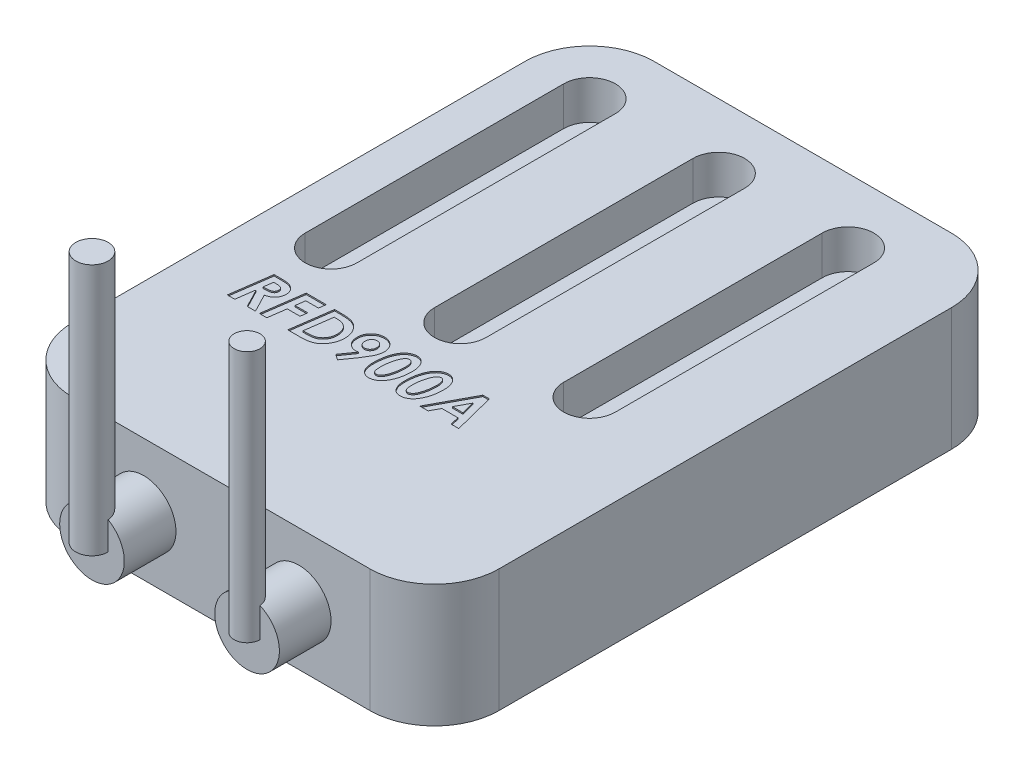
SolidWorks part; units mm, degrees
material "Alumina"
ref_plane "Front Plane" through (0, 0, 0) normal (0, 0, 1) x (1, 0, 0)
ref_plane "Top Plane" through (0, 0, 0) normal (0, 1, 0) x (1, 0, 0)
ref_plane "Right Plane" through (0, 0, 0) normal (1, 0, 0) x (0, 0, -1)
sketch "Sketch1" plane through (0, 0, 0) normal (0, 1, 0) x (1, 0, 0)
  line L1 (-16.5, -22.5) -> (16.5, -22.5)
  line L2 (-16.5, -22.5) -> (-16.5, 22.5)
  line L3 (-16.5, 22.5) -> (16.5, 22.5)
  line L4 (16.5, -22.5) -> (16.5, 22.5)
  line L5 (-16.5, -22.5) -> (16.5, 22.5) construction
  line L6 (-16.5, 22.5) -> (16.5, -22.5) construction
  point P0 (0, 0)
  dimension "D1" = 33
  dimension "D2" = 45
extrude "Boss-Extrude1" add sketch "Sketch1" along normal blind 9.5
fillet "Fillet1" radius 5 4 edges at (16.5, 4.75, -22.5) (-16.5, 4.75, -22.5) (-16.5, 4.75, 22.5) (16.5, 4.75, 22.5)
sketch "Sketch2" plane through (0, 0, 22.5) normal (0, 0, 1) x (1, 0, 0)
  line L0 (-11.5, 9.5) -> (11.5, 9.5) construction
  line L1 (0, 0) -> (0, 9.5) construction
  circle A0 centre (6, 4.5) radius 2.5
  circle A1 centre (-6, 4.5) radius 2.5
  dimension "D1" = 5
  dimension "D2" = 6
  dimension "D3" = 5
extrude "Boss-Extrude2" add sketch "Sketch2" along normal blind 4
sketch "Sketch3" plane through (0, 9.5, 0) normal (0, 1, 0) x (1, 0, 0)
  line L0 (-11.5, 17.5) -> (-11.5, -2.5) construction
  line L1 (-9.5, 17.5) -> (-9.5, -2.5)
  line L2 (-13.5, 17.5) -> (-13.5, -2.5)
  line L3 (11.5, 22.5) -> (-11.5, 22.5) construction
  line L4 (-16.5, 17.5) -> (-16.5, -17.5) construction
  line L5 (-3.5, 17.5) -> (-3.5, -2.5)
  line L6 (0.5, 17.5) -> (0.5, -2.5)
  line L7 (-1.5, 17.5) -> (-1.5, -2.5) construction
  line L8 (6.5, 17.5) -> (6.5, -2.5)
  line L9 (10.5, 17.5) -> (10.5, -2.5)
  line L10 (8.5, 17.5) -> (8.5, -2.5) construction
  arc A0 (-9.5, 17.5) -> (-13.5, 17.5) centre (-11.5, 17.5) ccw
  arc A1 (-13.5, -2.5) -> (-9.5, -2.5) centre (-11.5, -2.5) ccw
  arc A2 (0.5, 17.5) -> (-3.5, 17.5) centre (-1.5, 17.5) ccw
  arc A3 (-3.5, -2.5) -> (0.5, -2.5) centre (-1.5, -2.5) ccw
  arc A4 (10.5, 17.5) -> (6.5, 17.5) centre (8.5, 17.5) ccw
  arc A5 (6.5, -2.5) -> (10.5, -2.5) centre (8.5, -2.5) ccw
  point P2 (-11.5, 7.5)
  point P14 (-1.5, 7.5)
  point P21 (8.5, 7.5)
  dimension "D1" = 20
  dimension "D2" = 5
  dimension "D3" = 4
  dimension "D4" = 3
  dimension "D5" = 3
extrude "Cut-Extrude1" cut sketch "Sketch3" against normal blind 3
sketch "Sketch4" plane through (0, 9.5, 0) normal (0, 1, 0) x (1, 0, 0)
  text T0 "<b><i>RFD900A</i></b>"
extrude "Cut-Extrude2" cut sketch "Sketch4" against normal blind 0.1
sketch "Sketch5" plane through (0, 0, 26.5) normal (0, 0, 1) x (1, 0, 0)
  line L0 (-6, 4.5) -> (-6, 24.0024)
sweep "Sweep1" add path "Sketch5" circular profile diameter 2.5 parameters "D3"=2.5
sketch "Sketch19" plane through (0, 0, 26.5) normal (0, 0, 1) x (1, 0, 0)
  line L0 (6, 4.5) -> (6, 24.0024)
sweep "Sweep2" add path "Sketch19" circular profile diameter 2 parameters "D3"=2
